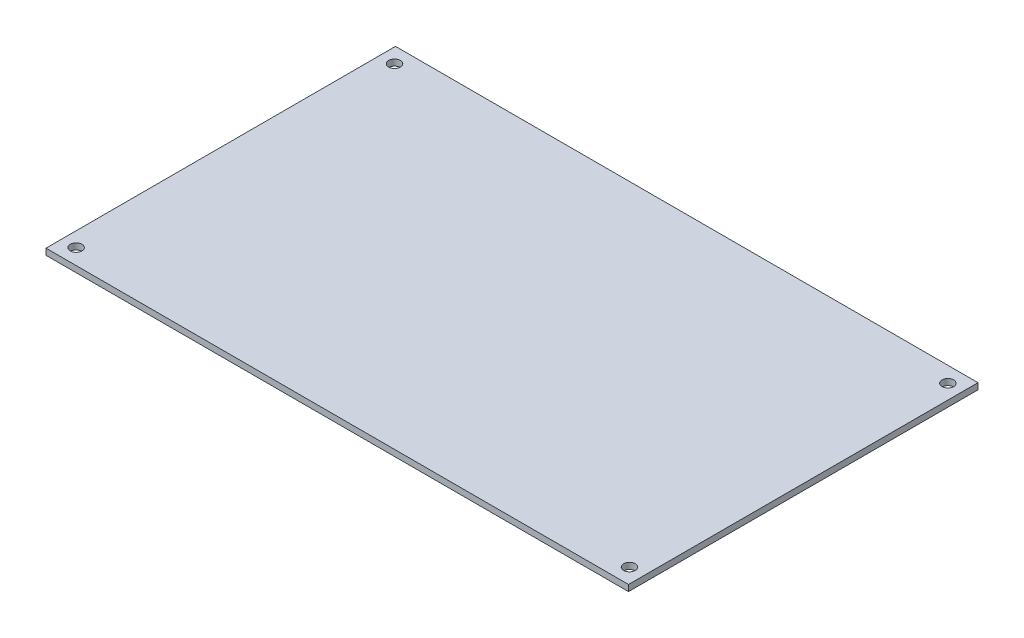
SolidWorks part; units mm, degrees
material "A-Glass Fiber"
ref_plane "Front Plane" through (0, 0, 0) normal (0, 0, 1) x (1, 0, 0)
ref_plane "Top Plane" through (0, 0, 0) normal (0, 1, 0) x (1, 0, 0)
ref_plane "Right Plane" through (0, 0, 0) normal (1, 0, 0) x (0, 0, -1)
other "Configuration Table"
sketch "Sketch1" plane through (0, 0, 0) normal (0, 1, 0) x (1, 0, 0)
  line L1 (75, -45) -> (-75, -45)
  line L2 (75, -45) -> (75, 45)
  line L3 (75, 45) -> (-75, 45)
  line L4 (-75, -45) -> (-75, 45)
  line L5 (75, -45) -> (-75, 45) construction
  line L6 (75, 45) -> (-75, -45) construction
  point P0 (0, 0)
  dimension "D1" = 90
  dimension "D2" = 150
extrude "Boss-Extrude1" add sketch "Sketch1" along normal blind 1.6
sketch "Sketch2" plane through (0, 1.6, 0) normal (0, 1, 0) x (1, 0, 0)
  line L1 (71.25, -41) -> (-71.25, -41) construction
  line L2 (71.25, -41) -> (71.25, 41) construction
  line L3 (71.25, 41) -> (-71.25, 41) construction
  line L4 (-71.25, -41) -> (-71.25, 41) construction
  line L5 (71.25, -41) -> (-71.25, 41) construction
  line L6 (71.25, 41) -> (-71.25, -41) construction
  circle A0 centre (-71.25, 41) radius 1.5
  circle A1 centre (-71.25, -41) radius 1.5
  circle A2 centre (71.25, -41) radius 1.5
  circle A3 centre (71.25, 41) radius 1.5
  point P0 (0, 0)
  dimension "D3" = 3
  dimension "D4" = 3
  dimension "D5" = 3
  dimension "D6" = 3
  dimension "D1" = 82
  dimension "D2" = 142.5
extrude "Cut-Extrude1" cut sketch "Sketch2" against normal blind 1.6
